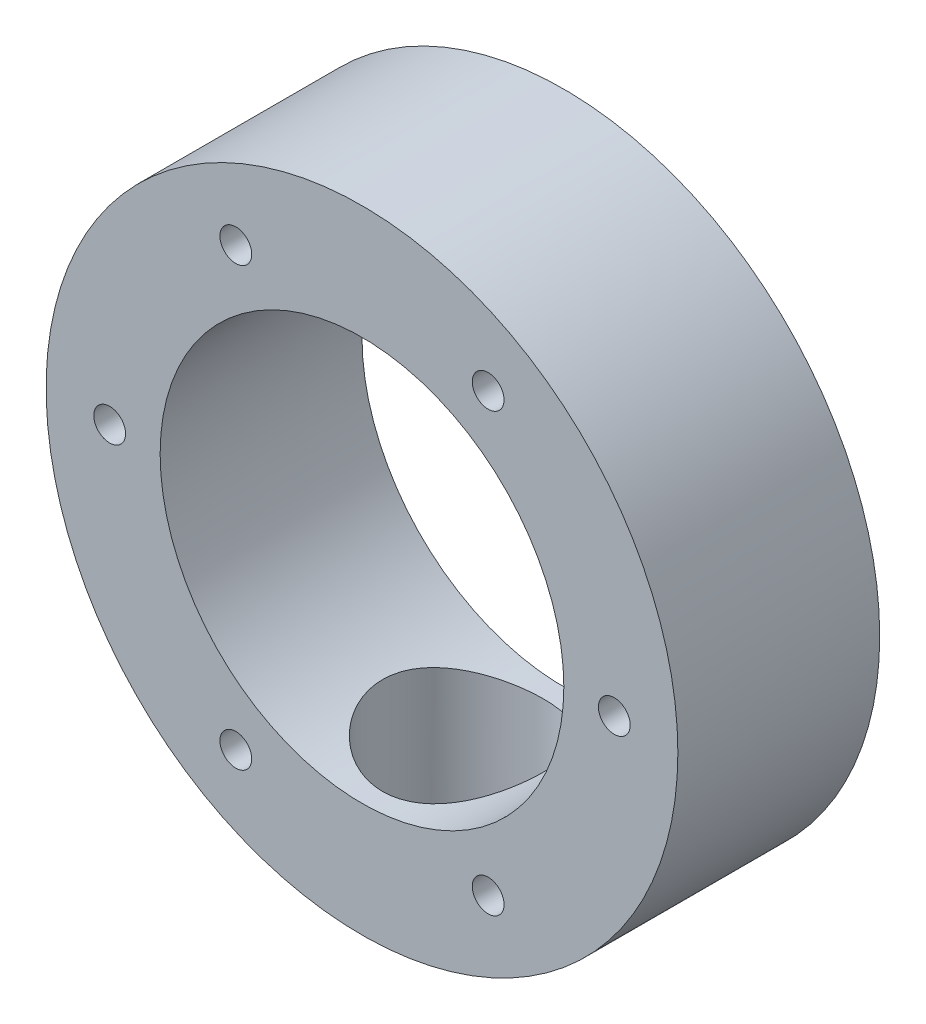
SolidWorks part; units mm, degrees
ref_plane "Front" through (0, 0, 0) normal (0, 0, 1) x (1, 0, 0)
ref_plane "Top" through (0, 0, 0) normal (0, 1, 0) x (1, 0, 0)
ref_plane "Right" through (0, 0, 0) normal (1, 0, 0) x (0, 0, -1)
sketch "Sketch1" plane through (0, 0, 0) normal (0, 0, 1) x (1, 0, 0)
  line L0 (0, 0) -> (-7.9375, 0) construction
  line L1 (-7.9375, 0) -> (-9.9375, 0) construction
  line L2 (-3.9687, 6.8741) -> (0, 0) construction
  circle A0 centre (0, 0) radius 9.9375
  circle A1 centre (0, 0) radius 6.35
  circle A2 centre (-7.9375, 0) radius 0.5
  circle A3 centre (-3.9687, 6.8741) radius 0.5
  circle A4 centre (3.9688, 6.8741) radius 0.5
  circle A5 centre (7.9375, 0) radius 0.5
  circle A6 centre (3.9687, -6.8741) radius 0.5
  circle A7 centre (-3.9688, -6.8741) radius 0.5
  dimension "D1" = 12.7
  dimension "D2" = 2
  dimension "D3" = 1
  dimension "D4" = 7.9375
  dimension "D6" = 60
  dimension "D5" = 6
extrude "Boss-Extrude1" add sketch "Sketch1" along normal blind 6.35
ref_plane "Plane1" through (0, -9.9375, 0) normal (0, -1, 0) x (1, 0, 0)
hole_wizard "#8 (0.199) Diameter Hole1" positions "Sketch4" profile "Sketch5" hole size "#8" standard "Ansi Inch"
sketch "Sketch4" plane through (0, -9.9375, 0) normal (0, -1, 0) x (1, 0, 0)
  line L0 (0, 0) -> (0, 6.35) construction
  line L1 (9.9375, 6.35) -> (-9.9375, 6.35) construction
  point P1 (0, 3.175)
sketch "Sketch5" plane through (0, -9.9375, 3.175) normal (1, 0, 0) x (0, 0, -1)
  line L0 (0, 0) -> (0, 9.8686)
  line L1 (0, 9.8686) -> (2.5273, 8.35)
  line L2 (2.5273, 8.35) -> (2.5273, 0)
  line L5 (2.5273, 0) -> (0, 0)
  line L10 (0, 9.8686) -> (-2.5273, 8.35) construction
  line L11 (0, -6.35) -> (0, 107.95) construction
  dimension "Hole Dia." = 5.0546
  dimension "Hole Depth" = 8.35
  dimension "Drill Angle" = 118
